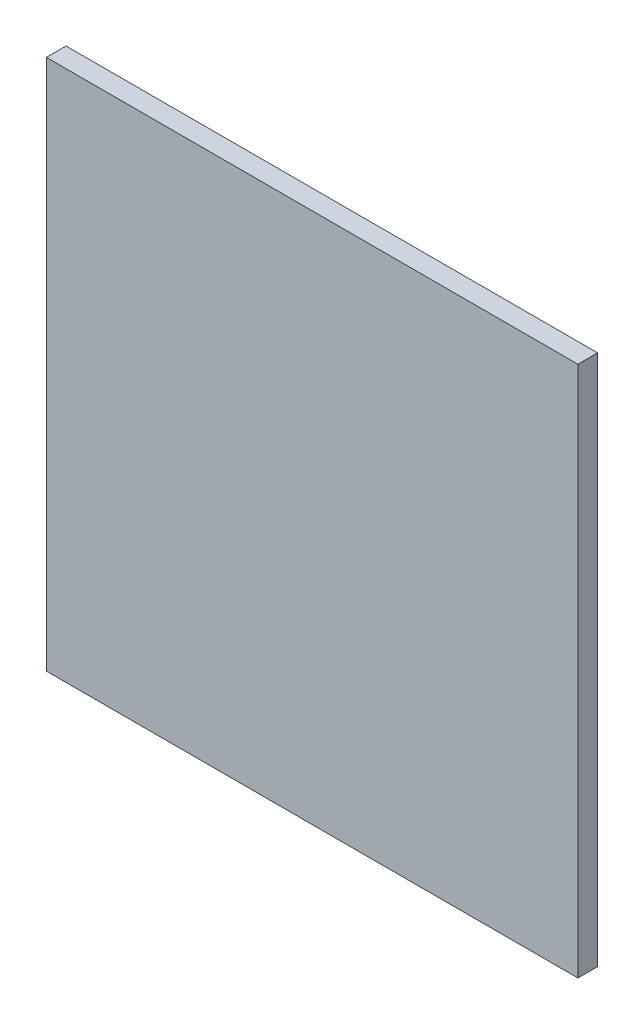
SolidWorks part; units mm, degrees
ref_plane "Front" through (0, 0, 0) normal (0, 0, 1) x (1, 0, 0)
ref_plane "Top" through (0, 0, 0) normal (0, 1, 0) x (1, 0, 0)
ref_plane "Right" through (0, 0, 0) normal (1, 0, 0) x (0, 0, -1)
sketch "Sketch1" plane through (0, 0, 0) normal (0, 0, 1) x (1, 0, 0)
  line L5 (-171.45, -171.45) -> (171.45, -171.45)
  line L6 (-171.45, -171.45) -> (-171.45, 171.45)
  line L7 (-171.45, 171.45) -> (171.45, 171.45)
  line L8 (171.45, -171.45) -> (171.45, 171.45)
  line L9 (-171.45, -171.45) -> (171.45, 171.45) construction
  line L10 (-171.45, 171.45) -> (171.45, -171.45) construction
  point P4 (0, 0)
  dimension "D1" = 342.9
  dimension "D2" = 342.9
extrude "Boss-Extrude1" add sketch "Sketch1" along normal blind 12.7
